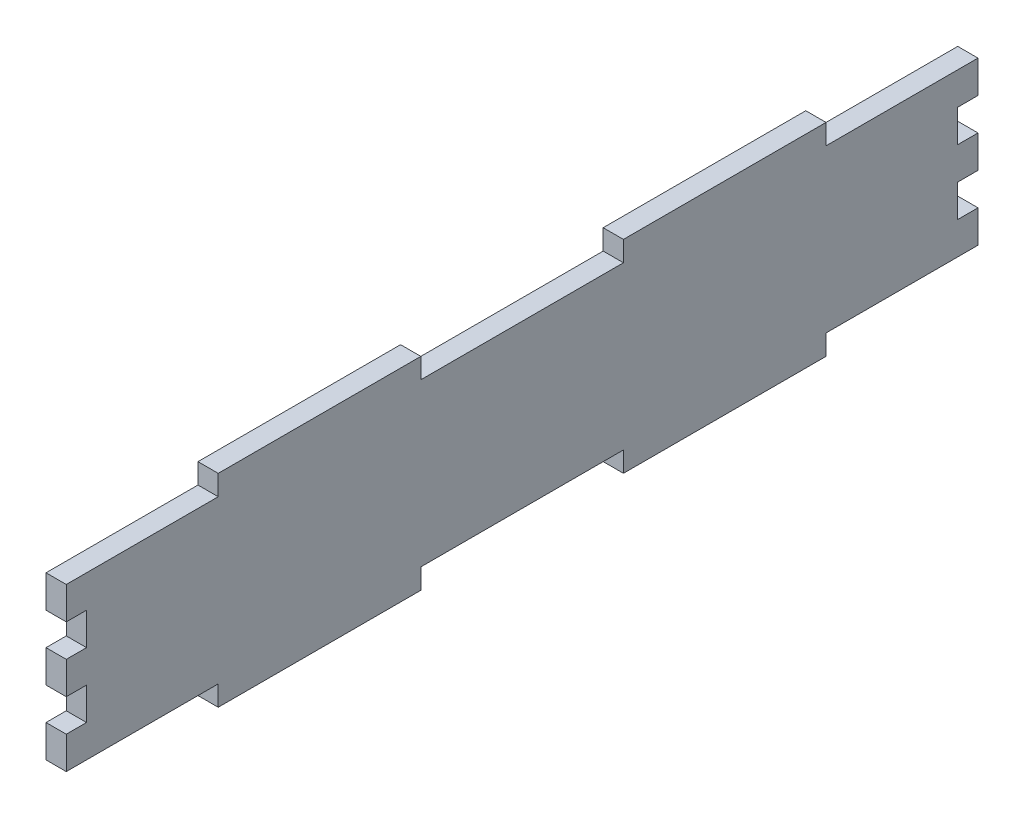
SolidWorks part; units mm, degrees
ref_plane "Front Plane" through (0, 0, 0) normal (0, 0, 1) x (1, 0, 0)
ref_plane "Top Plane" through (0, 0, 0) normal (0, 1, 0) x (1, 0, 0)
ref_plane "Right Plane" through (0, 0, 0) normal (1, 0, 0) x (0, 0, -1)
sketch "Sketch1" plane through (0, 0, 0) normal (1, 0, 0) x (0, 0, -1)
  line L1 (6.4504, 2.8223) -> (25.9504, 2.8223)
  line L3 (6.4504, 26.8223) -> (25.9504, 26.8223)
  line L7 (85.9504, 2.8223) -> (85.9504, -0.1777)
  line L8 (85.9504, -0.1777) -> (115.9504, -0.1777)
  line L9 (115.9504, -0.1777) -> (115.9504, 2.8223)
  line L10 (115.9504, 2.8223) -> (135.4504, 2.8223)
  line L11 (55.9504, 2.8223) -> (85.9504, 2.8223)
  line L36 (55.9504, -0.1777) -> (55.9504, 2.8223)
  line L37 (25.9504, -0.1777) -> (55.9504, -0.1777)
  line L38 (25.9504, 2.8223) -> (25.9504, -0.1777)
  line L48 (85.9504, 26.8223) -> (85.9504, 29.8223)
  line L49 (85.9504, 29.8223) -> (115.9504, 29.8223)
  line L50 (115.9504, 29.8223) -> (115.9504, 26.8223)
  line L51 (55.9504, 29.8223) -> (55.9504, 26.8223)
  line L52 (25.9504, 29.8223) -> (55.9504, 29.8223)
  line L70 (25.9504, 26.8223) -> (25.9504, 29.8223)
  line L71 (115.9504, 26.8223) -> (135.4504, 26.8223)
  line L72 (55.9504, 26.8223) -> (85.9504, 26.8223)
  line L73 (135.4504, 2.8223) -> (138.4504, 2.8223)
  line L74 (138.4504, 2.8223) -> (138.4504, 7.6223)
  line L75 (138.4504, 7.6223) -> (135.4504, 7.6223)
  line L76 (135.4504, 12.4223) -> (138.4504, 12.4223)
  line L77 (138.4504, 12.4223) -> (138.4504, 17.2223)
  line L78 (138.4504, 17.2223) -> (135.4504, 17.2223)
  line L79 (135.4504, 22.0223) -> (138.4504, 22.0223)
  line L80 (138.4504, 22.0223) -> (138.4504, 26.8223)
  line L81 (138.4504, 26.8223) -> (135.4504, 26.8223)
  line L82 (135.4504, 7.6223) -> (135.4504, 12.4223)
  line L83 (135.4504, 17.2223) -> (135.4504, 22.0223)
  line L84 (3.4504, 7.6223) -> (6.4504, 7.6223)
  line L85 (6.4504, 2.8223) -> (3.4504, 2.8223)
  line L86 (3.4504, 2.8223) -> (3.4504, 7.6223)
  line L87 (6.4504, 12.4223) -> (3.4504, 12.4223)
  line L88 (3.4504, 12.4223) -> (3.4504, 17.2223)
  line L89 (3.4504, 17.2223) -> (6.4504, 17.2223)
  line L90 (6.4504, 22.0223) -> (3.4504, 22.0223)
  line L91 (3.4504, 22.0223) -> (3.4504, 26.8223)
  line L92 (3.4504, 26.8223) -> (6.4504, 26.8223)
  line L93 (6.4504, 7.6223) -> (6.4504, 12.4223)
  line L94 (6.4504, 17.2223) -> (6.4504, 22.0223)
  dimension "D2" = 19.5
  dimension "D3" = 4.8
  dimension "D4" = 30
  dimension "D5" = 3
  dimension "D6" = 2
  dimension "D7" = 3
  dimension "D8" = 3
  dimension "D9" = 3
  dimension "D10" = 3
  dimension "D11" = 30
  dimension "D13" = 3
  dimension "D14" = 4.8
  dimension "D12" = 2
extrude "Boss-Extrude1" add sketch "Sketch1" along normal blind 3
